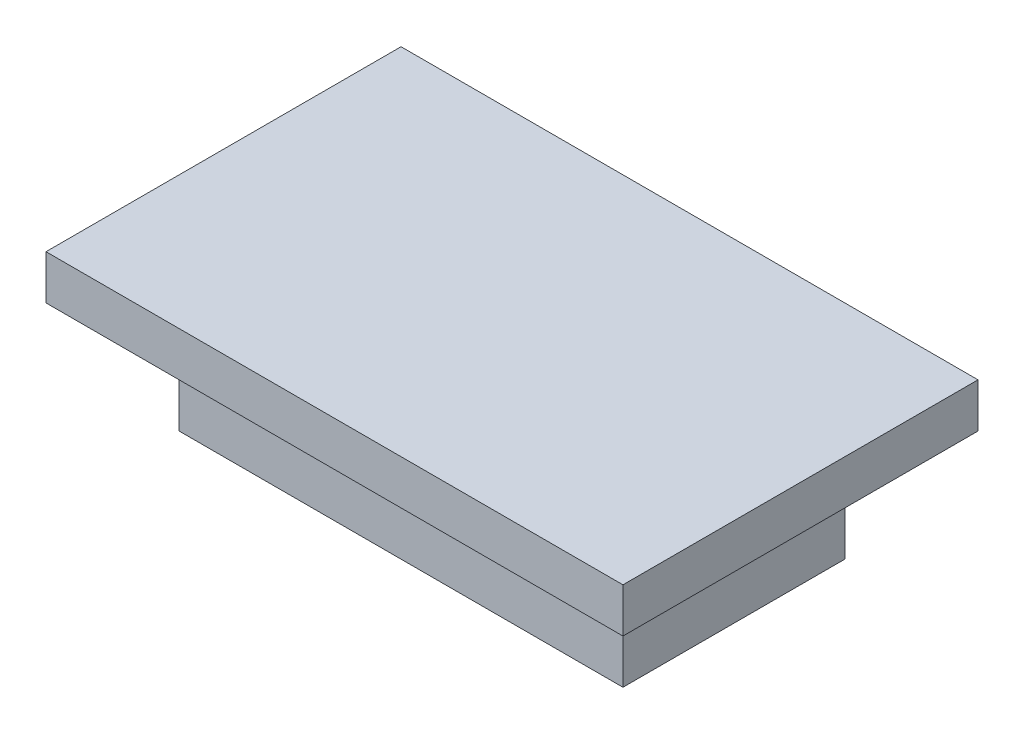
SolidWorks part; units mm, degrees
material "Silicon Rubber"
ref_plane "Front Plane" through (0, 0, 0) normal (0, 0, 1) x (1, 0, 0)
ref_plane "Top Plane" through (0, 0, 0) normal (0, 1, 0) x (1, 0, 0)
ref_plane "Right Plane" through (0, 0, 0) normal (1, 0, 0) x (0, 0, -1)
sketch "Sketch1" plane through (0, 0, 0) normal (0, 1, 0) x (1, 0, 0)
  line L1 (0, 0) -> (20, 0)
  line L2 (0, 0) -> (0, 10)
  line L3 (0, 10) -> (20, 10)
  line L4 (20, 0) -> (20, 10)
extrude "Boss-Extrude1" add sketch "Sketch1" along normal blind 5
sketch "Sketch2" plane through (0, 5, 0) normal (0, 1, 0) x (1, 0, 0)
  line L0 (0, 10) -> (-3, 10)
  line L1 (-3, 10) -> (-3, 13)
  line L2 (-3, 10) -> (-3, -3)
  line L4 (-3, -3) -> (23, -3)
  line L6 (23, -3) -> (23, 13)
  line L7 (23, 13) -> (-3, 13)
  dimension "D1" = 13
  dimension "D2" = 26
extrude "Boss-Extrude2" add sketch "Sketch2" along normal blind 2
